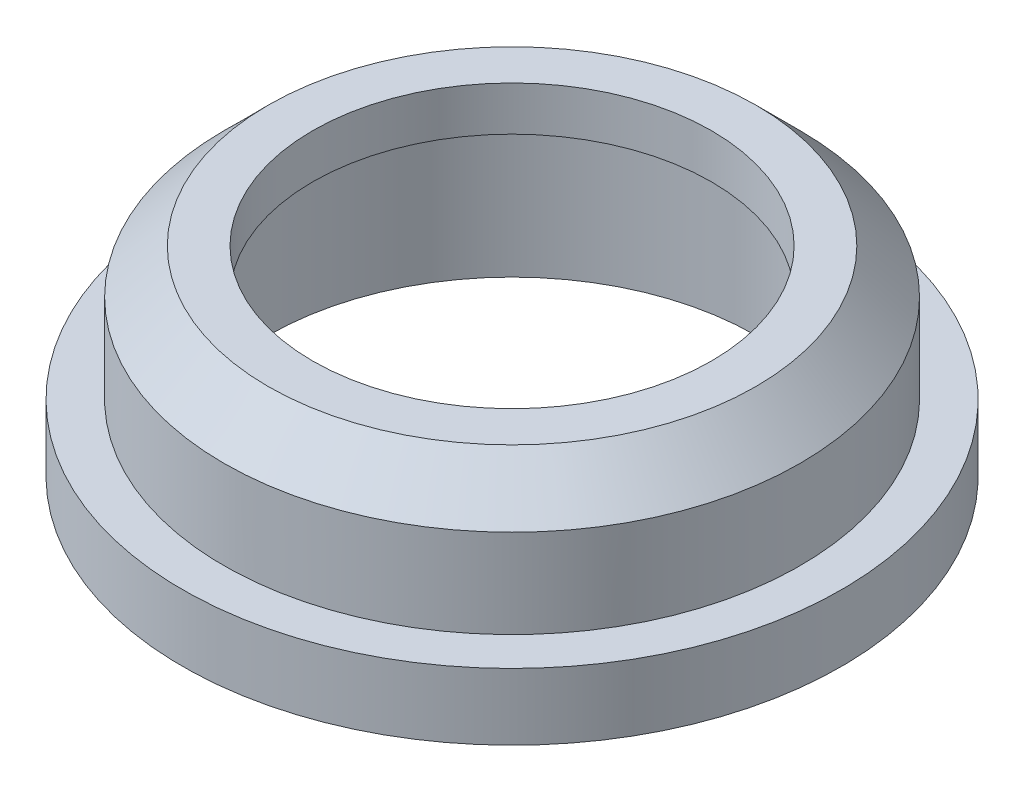
SolidWorks part; units mm, degrees
ref_plane "Alzado" through (0, 0, 0) normal (0, 0, 1) x (1, 0, 0)
ref_plane "Planta" through (0, 0, 0) normal (0, 1, 0) x (1, 0, 0)
ref_plane "Vista lateral" through (0, 0, 0) normal (1, 0, 0) x (0, 0, -1)
sketch "Croquis1" plane through (0, 0, 0) normal (0, 1, 0) x (1, 0, 0)
  line L0 (65, 10) -> (70, 15)
  line L1 (-65, -20) -> (65, -20)
  line L2 (-65, -20) -> (-65, 20)
  line L3 (-65, 20) -> (65, 20)
  line L4 (65, -20) -> (65, -10)
  line L5 (-65, -20) -> (65, 20) construction
  line L6 (-65, 20) -> (65, -20) construction
  line L7 (70, 15) -> (70, -15)
  line L8 (70, -15) -> (65, -10)
  line L9 (65, 10) -> (65, 20)
  line L10 (0, 0) -> (77.1384, 0) construction
  line L12 (10, 9.5) -> (40, 9.5)
  line L13 (10, 9.5) -> (10, 12.5)
  line L14 (10, 12.5) -> (40, 12.5)
  line L15 (40, 9.5) -> (40, 12.5)
  line L16 (10, 9.5) -> (40, 12.5) construction
  line L17 (10, 12.5) -> (40, 9.5) construction
  line L18 (10, -12.5) -> (40, -12.5)
  line L19 (10, -12.5) -> (10, -9.5)
  line L20 (10, -9.5) -> (40, -9.5)
  line L21 (40, -12.5) -> (40, -9.5)
  line L22 (10, -12.5) -> (40, -9.5) construction
  line L23 (10, -9.5) -> (40, -12.5) construction
  circle A2 centre (-50.1299, 0) radius 11
  circle A3 centre (-50.1299, 0) radius 12.5 construction
  circle A4 centre (-28.5951, 0) radius 2
  circle A5 centre (-13.5951, 0) radius 2
  circle A6 centre (50, 0) radius 2
  point P0 (0, 0)
  point P8 (70, 0)
  point P19 (25, 11)
  point P35 (25, -11)
  dimension "D8" = 22
  dimension "D12" = 25
  dimension "D13" = 4
  dimension "D14" = 4
  dimension "D17" = 4
  dimension "D1" = 130
  dimension "D2" = 45
  dimension "D3" = 45
  dimension "D4" = 20
  dimension "D5" = 30
  dimension "D6" = 40
  dimension "D9" = 3
  dimension "D10" = 30
  dimension "D11" = 40
  dimension "D15" = 15
  dimension "D16" = 10
  dimension "D18" = 12.5
  dimension "D19" = 12.5
extrude "Saliente-Extruir1" add sketch "Croquis1" along normal blind 3
sketch "Croquis2" plane through (0, 3, 0) normal (0, 1, 0) x (1, 0, 0)
  circle A0 centre (-50.1299, 0) radius 11
  circle A1 centre (-50.1299, 0) radius 13
  dimension "D1" = 2
extrude "Saliente-Extruir2" add sketch "Croquis2" along normal blind 4
sketch "Croquis3" plane through (0, 7, 0) normal (0, 1, 0) x (1, 0, 0)
  circle A0 centre (-50.1299, 0) radius 13
  circle A1 centre (-50.1299, 0) radius 9
  dimension "D1" = 18
extrude "Saliente-Extruir3" add sketch "Croquis3" along normal blind 2
chamfer "Chaflán1" distance 2 angle 45 1 edges at (-50.1299, 9, 13)
chamfer "Chaflán2" distance 10 angle 45 2 edges at (-65, 1.5, 20) (-65, 1.5, -20)
sketch "Croquis4" plane through (0, 3, 0) normal (0, 1, 0) x (1, 0, 0)
  circle A0 centre (-50.1299, 0) radius 14.8701
extrude "Cortar-Extruir1" cut sketch "Croquis4" against normal blind 10 and the other way blind 10 flip side to cut
